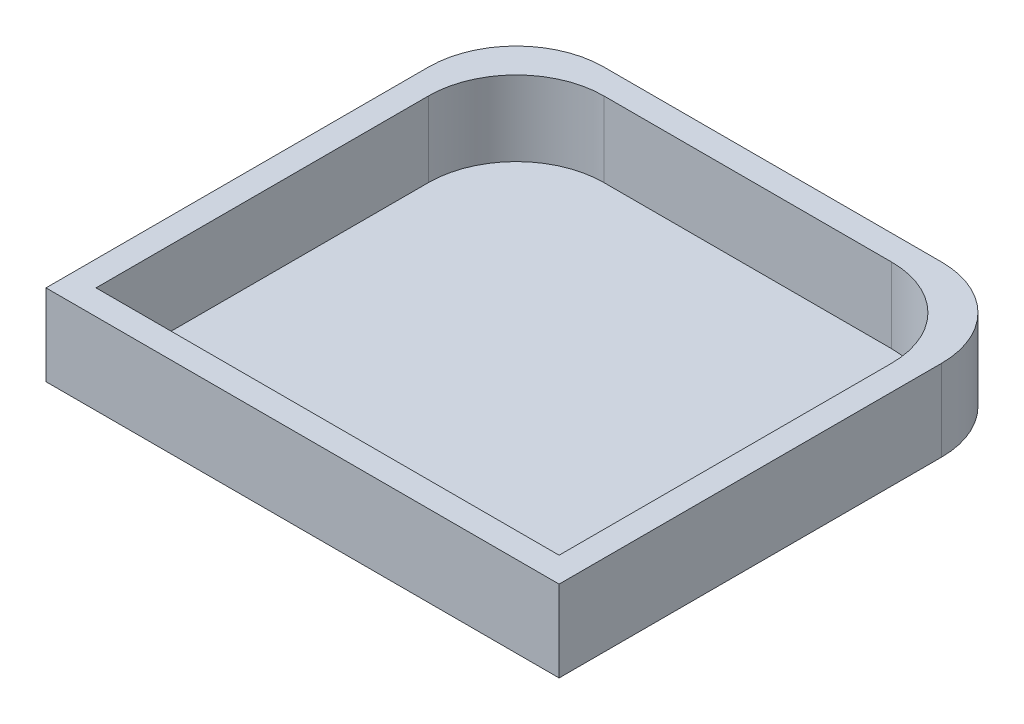
SolidWorks part; units mm, degrees
ref_plane "Front Plane" through (0, 0, 0) normal (0, 0, 1) x (1, 0, 0)
ref_plane "Top Plane" through (0, 0, 0) normal (0, 1, 0) x (1, 0, 0)
ref_plane "Right Plane" through (0, 0, 0) normal (1, 0, 0) x (0, 0, -1)
sketch "Sketch3" plane through (0, 0, 0) normal (0, 1, 0) x (1, 0, 0)
  line L1 (-41.015, -37.585) -> (41.015, -37.585)
  line L2 (-41.015, -37.585) -> (-41.015, 23.585)
  line L3 (-27.015, 37.585) -> (27.015, 37.585)
  line L4 (41.015, -37.585) -> (41.015, 23.585)
  line L5 (-41.015, -37.585) -> (41.015, 37.585) construction
  line L6 (-41.015, 37.585) -> (41.015, -37.585) construction
  arc A0 (41.015, 23.585) -> (27.015, 37.585) centre (27.015, 23.585) ccw
  arc A1 (-27.015, 37.585) -> (-41.015, 23.585) centre (-27.015, 23.585) ccw
  point P0 (0, 0)
  dimension "D3" = 14
  dimension "D1" = 82.03
  dimension "D2" = 75.17
extrude "Boss-Extrude1" add sketch "Sketch3" along normal blind 13
sketch "Sketch4" plane through (0, 13, 0) normal (0, 1, 0) x (1, 0, 0)
  line L0 (-41.015, 23.585) -> (-41.015, -37.585) construction
  line L1 (-37.015, -33.585) -> (37.015, -33.585)
  line L2 (-37.015, -33.585) -> (-37.015, 19.585)
  line L3 (-23.015, 33.585) -> (23.015, 33.585)
  line L4 (37.015, -33.585) -> (37.015, 19.585)
  line L5 (-37.015, -33.585) -> (37.015, 33.585) construction
  line L6 (-37.015, 33.585) -> (37.015, -33.585) construction
  line L7 (41.015, -37.585) -> (41.015, 23.585) construction
  line L8 (27.015, 37.585) -> (-27.015, 37.585) construction
  line L9 (-41.015, -37.585) -> (41.015, -37.585) construction
  arc A0 (37.015, 19.585) -> (23.015, 33.585) centre (23.015, 19.585) ccw
  arc A1 (-23.015, 33.585) -> (-37.015, 19.585) centre (-23.015, 19.585) ccw
  point P0 (0, 0)
  dimension "D5" = 14
  dimension "D1" = 4
  dimension "D2" = 4
  dimension "D3" = 4
  dimension "D4" = 4
extrude "Cut-Extrude1" cut sketch "Sketch4" against normal blind 12
